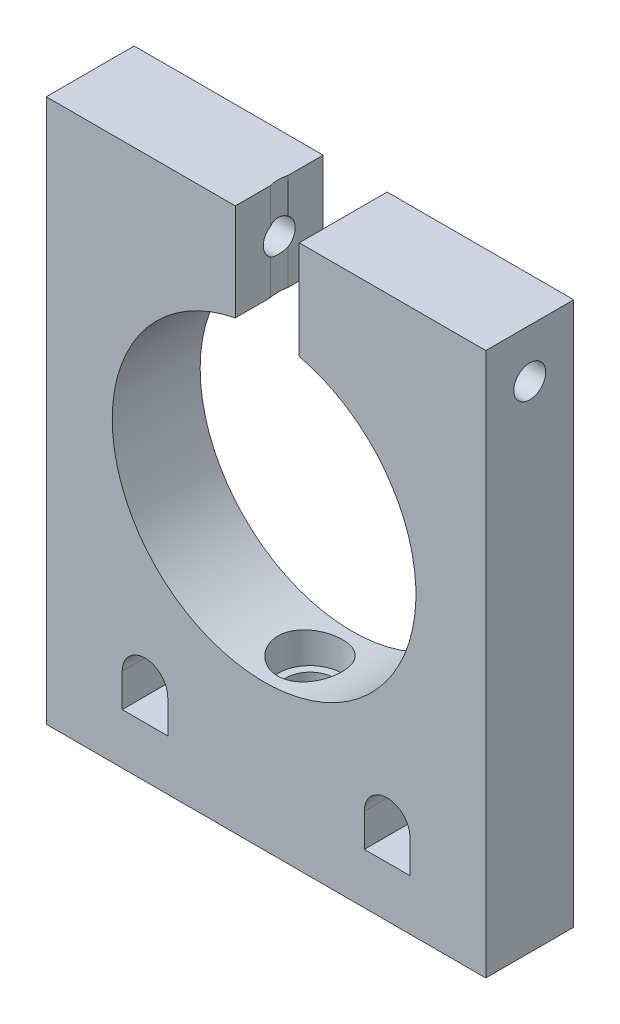
SolidWorks part; units mm, degrees
ref_plane "Front Plane" through (0, 0, 0) normal (0, 0, 1) x (1, 0, 0)
ref_plane "Top Plane" through (0, 0, 0) normal (0, 1, 0) x (1, 0, 0)
ref_plane "Right Plane" through (0, 0, 0) normal (1, 0, 0) x (0, 0, -1)
sketch "Sketch1" plane through (0, 0, 0) normal (0, 0, 1) x (1, 0, 0)
  line L1 (-55, 41.9737) -> (0, 41.9737)
  line L2 (-55, 41.9737) -> (-55, 23.9737)
  line L3 (-55, 23.9737) -> (0, 23.9737)
  line L4 (0, 41.9737) -> (0, 23.9737)
  line L5 (-55, 41.9737) -> (0, 23.9737) construction
  line L6 (-55, 23.9737) -> (0, 41.9737) construction
  dimension "D1" = 55
  dimension "D2" = 18
extrude "Boss-Extrude1" add sketch "Sketch1" along normal blind 15
sketch "Sketch2" plane through (0, 41.9737, 0) normal (0, 1, 0) x (1, 0, 0)
  line L0 (0, -15) -> (0, 0) construction
  line L1 (-55, 0) -> (0, 0)
  line L2 (-55, 0) -> (-55, -15)
  line L3 (-55, -15) -> (0, -15)
  line L4 (0, 0) -> (0, -15)
  dimension "D1" = 15
extrude "Boss-Extrude2" add sketch "Sketch2" along normal blind 50 contours L2 L1 L4 L3
sketch "Sketch14" plane through (0, 0, 15) normal (0, 0, 1) x (1, 0, 0)
  line L0 (-55, 23.9737) -> (0, 23.9737) construction
  circle A0 centre (-27.7462, 61.1737) radius 19
  dimension "D1" = 37.2
extrude "Cut-Extrude14" cut sketch "Sketch14" against normal blind 21 contours A0
sketch "Sketch6" plane through (0, 0, 15) normal (0, 0, 1) x (1, 0, 0)
  line L0 (-27.5, 60.9737) -> (-27.3504, 79.8942)
  line L2 (-31.3504, 93.8365) -> (-23.3504, 93.8365)
  line L3 (-31.3504, 93.8365) -> (-31.3504, 65.952)
  line L4 (-31.3504, 65.952) -> (-23.3504, 65.952)
  line L5 (-23.3504, 93.8365) -> (-23.3504, 65.952)
  line L6 (-31.3504, 93.8365) -> (-23.3504, 65.952) construction
  line L7 (-31.3504, 65.952) -> (-23.3504, 93.8365) construction
  arc A0 (-23.5, 42.3044) -> (-31.5, 42.3363) centre (-27.426, 60.8944) ccw construction
  dimension "D1" = 8
extrude "Cut-Extrude3" cut sketch "Sketch6" against normal blind 50 contours L2 L5 L4 L3
sketch "Sketch9" plane through (-55, 0, 0) normal (-1, 0, 0) x (0, 0, 1)
  circle A0 centre (5.5, 85.8887) radius 2
  dimension "D1" = 4
extrude "Cut-Extrude5" cut sketch "Sketch9" against normal blind 55
sketch "Sketch10" plane through (0, 0, 15) normal (0, 0, 1) x (1, 0, 0)
  line L4 (-9.5, 30.3118) -> (-9.5, 34.4737)
  line L5 (-15.2, 34.4737) -> (-15.2, 30.3118)
  line L6 (-45.5, 30.3118) -> (-39.8, 30.3118)
  line L7 (-45.5, 30.3118) -> (-45.5, 34.4737)
  line L8 (-39.8, 34.4737) -> (-39.8, 30.3118)
  line L10 (-15.2, 30.3118) -> (-9.5, 30.3118)
  arc A0 (-9.5, 34.4737) -> (-15.2, 34.4737) centre (-12.35, 34.4737) ccw
  arc A1 (-45.5, 34.4737) -> (-39.8, 34.4737) centre (-42.65, 34.4737) cw
  dimension "D4" = 5.7
extrude "Cut-Extrude6" cut sketch "Sketch10" against normal blind 55 contours L8 L6 L7 A1 | L4 A0 L5 L10
sketch "Sketch16" plane through (0, 23.9737, 0) normal (0, -1, 0) x (-1, 0, 0)
  line L0 (0, -15) -> (0, 0) construction
  line L1 (55, -15) -> (0, -15)
  line L2 (55, -15) -> (55, -11)
  line L3 (55, -11) -> (0, -11)
  line L4 (0, -15) -> (0, -11)
  dimension "D1" = 4
extrude "Cut-Extrude16" cut sketch "Sketch16" against normal blind 73
sketch "Sketch17" plane through (0, 23.9737, 0) normal (0, -1, 0) x (-1, 0, 0)
  line L0 (55, 0) -> (0, 0) construction
  circle A0 centre (27.5, -5.5) radius 3
  point P6 (0, 0)
  dimension "D3" = 6
  dimension "D1" = 5.5
  dimension "D2" = 27.5
extrude "Cut-Extrude17" cut sketch "Sketch17" against normal blind 89
ref_plane "Plane5" through (0, 38.5, 0) normal (0, 1, 0) x (1, 0, 0)
sketch "Sketch18" plane through (0, 38.5, 0) normal (0, 1, 0) x (1, 0, 0)
  circle A0 centre (-27.5, -5.5) radius 4
  dimension "D1" = 8
extrude "Cut-Extrude18" cut sketch "Sketch18" along normal blind 89
